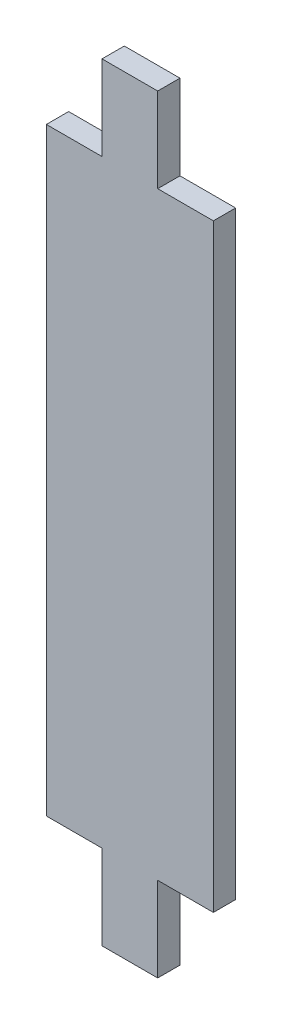
SolidWorks part; units mm, degrees
ref_plane "前视基准面" through (0, 0, 0) normal (0, 0, 1) x (1, 0, 0)
ref_plane "上视基准面" through (0, 0, 0) normal (0, 1, 0) x (1, 0, 0)
ref_plane "右视基准面" through (0, 0, 0) normal (1, 0, 0) x (0, 0, -1)
sketch "草图1" plane through (0, 0, 0) normal (0, 1, 0) x (1, 0, 0)
  line L0 (-6.8519, 0) -> (14.1358, 0) construction
  line L1 (0, 7.3765) -> (0, -7.5926) construction
  line L3 (-10.7099, 0) -> (4.2901, 0)
  line L4 (-10.7099, 0) -> (-10.7099, -2)
  line L5 (-10.7099, -2) -> (4.2901, -2)
  line L6 (4.2901, 0) -> (4.2901, -2)
  dimension "D1" = 15
  dimension "D2" = 2
extrude "凸台-拉伸1" add sketch "草图1" along normal blind 69
sketch "草图2" plane through (0, 0, 0) normal (0, 0, -1) x (-1, 0, 0)
  line L0 (-35.3813, 34.5) -> (57.0289, 34.5) construction
  line L1 (-4.2901, 69) -> (-4.2901, 0) construction
  line L2 (10.7099, 69) -> (5.7099, 69)
  line L3 (-4.2901, 0) -> (0.7099, 0)
  line L4 (-4.2901, 0) -> (-4.2901, 7.6)
  line L5 (-4.2901, 7.6) -> (0.7099, 7.6)
  line L6 (0.7099, 0) -> (0.7099, 7.6)
  line L7 (10.7099, 0) -> (5.7099, 0)
  line L8 (10.7099, 0) -> (10.7099, 7.6)
  line L9 (10.7099, 7.6) -> (5.7099, 7.6)
  line L10 (5.7099, 0) -> (5.7099, 7.6)
  line L11 (10.7099, 69) -> (10.7099, 61.4)
  line L12 (10.7099, 61.4) -> (5.7099, 61.4)
  line L13 (5.7099, 69) -> (5.7099, 61.4)
  line L14 (-4.2901, 69) -> (-4.2901, 61.4)
  line L15 (-4.2901, 69) -> (0.7099, 69)
  line L16 (0.7099, 69) -> (0.7099, 61.4)
  line L17 (-4.2901, 61.4) -> (0.7099, 61.4)
  point P4 (-4.2901, 34.5)
  point P22 (7.4045, 8.5086)
  point P24 (-1.7901, 7.6)
  dimension "D3" = 53.8
  dimension "D4" = 53.8
  dimension "D1" = 5
  dimension "D2" = 5
extrude "切除-拉伸1" cut sketch "草图2" against normal blind 69
